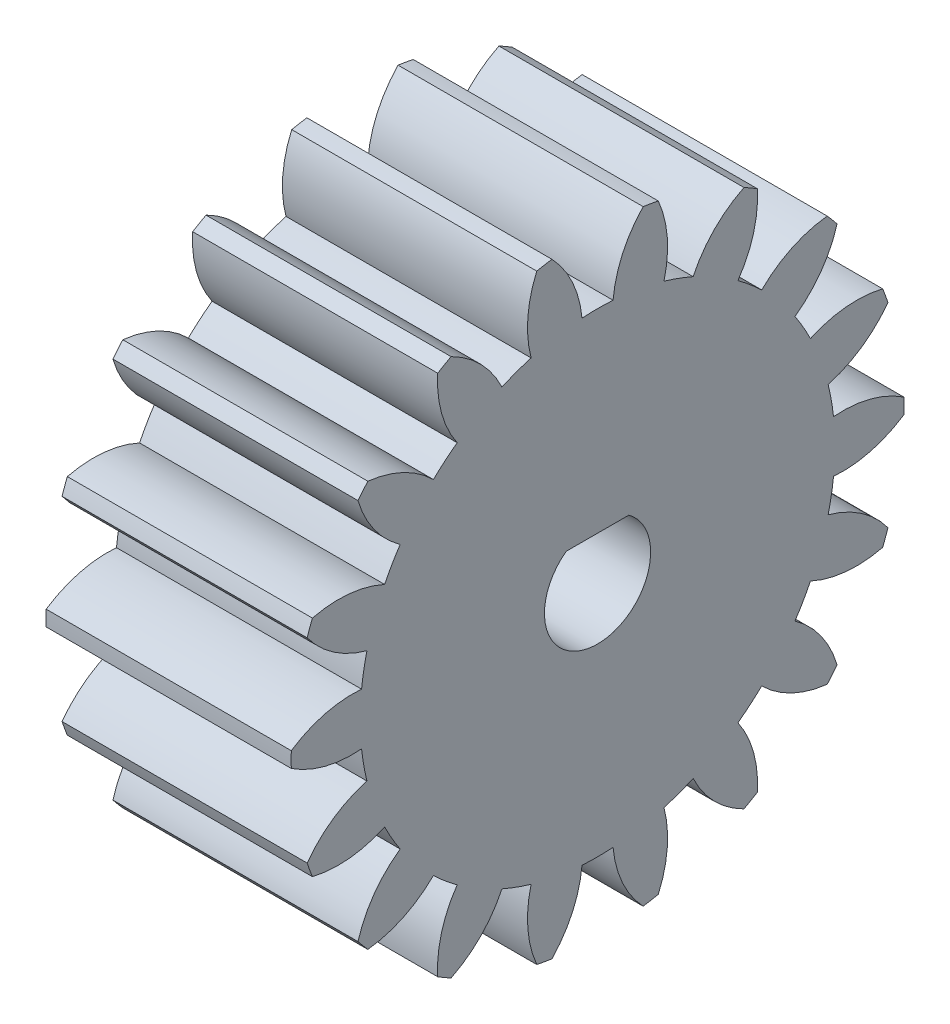
SolidWorks part; units mm, degrees
ref_plane "Plane1" through (0, 0, 0) normal (0, 0, 1) x (1, 0, 0)
ref_plane "Plane2" through (0, 0, 0) normal (0, 1, 0) x (1, 0, 0)
ref_plane "Plane3" through (0, 0, 0) normal (1, 0, 0) x (0, 0, -1)
other "Configuration Table"
sketch "HoldingSke" plane through (0, 0, 0) normal (0, 1, 0) x (1, 0, 0)
  line L0 (0, 0) -> (0.634, -0.206)
  line L1 (-15, 0) -> (100, 0) construction
  line L2 (0, 0) -> (-2.1039, 2.3779)
  line L3 (0, 0) -> (-11.863, 4.5341)
  line L4 (0, 0) -> (8.2133, 2.6687)
  line L5 (0, 0) -> (-46.8476, -17.4728)
  line L6 (0, 0) -> (-9.9476, -6.7116)
  line L7 (-2.1039, 2.3779) -> (8.6586, 51.2059)
  line L8 (-76.2, 54.61) -> (-75.3, 54.61)
  line L9 (-71.009, 38.7566) -> (-53.1078, 45.2721)
  line L10 (-76.2, 71.12) -> (104.1128, 71.12)
  line L11 (0, 0) -> (-12, 0)
  line L12 (-76.2, 101.6) -> (-76.147, 101.6)
  line L13 (24.9733, 27.94) -> (52.9518, 28.4284)
  line L14 (24.9733, 27.94) -> (24.9743, 27.94)
  line L15 (24.9733, 27.94) -> (100.4006, 29.5858)
  line L16 (-63.627, -1.5) -> (-12.827, -1.5)
  circle A0 centre (0, 0) radius 2.5
  circle A1 centre (0, 0) radius 11.624
  circle A2 centre (0, 0) radius 37.5
  circle A3 centre (0, 0) radius 2.5
  dimension "MHD" = 23.248
  dimension "Hub_dia" = 75
  dimension "Bore" = 5
  dimension "MBD" = 5
  dimension "Num_teeth" = 18
  dimension "Pitch" = 0.6667
  dimension "Overall_len" = 50
  dimension "Show_teeth" = 18
  dimension "Thickness" = 12
  dimension "OAL" = 50.0001
  dimension "T_dim" = 0.9
  dimension "Ap" = 20
  dimension "H" = 19.05
  dimension "Pitch_radius" = 180.3128
  dimension "Width" = 12
  dimension "Backlash" = 0.053
  dimension "Addendum_fac" = 1
  dimension "Dedendum_fac" = 1.25
  dimension "Clearance_fac" = 0.25
  dimension "Dedendum_add" = 0.001
  dimension "Module" = 1.5
sketch "BasProSke" plane through (0, 0, 0) normal (0, 1, 0) x (1, 0, 0)
  line L0 (-10, 0) -> (60, 0) construction
  line L1 (0, 0) -> (0, 15)
  line L2 (0, 0) -> (12, 0)
  line L3 (12, 0) -> (12, 15)
  line L4 (12, 15) -> (0, 15)
  dimension "Thickness" = 12
  dimension "Diameter" = 30
revolve "Base-Revolve" add sketch "BasProSke" angle 360 about L0
sketch "TooCutSke" plane through (0, 0, 0) normal (1, 0, 0) x (0, 0, -1)
  line L1 (0, 0) -> (0, 107) construction
  line L2 (0, 0) -> (-1.2693, 13.4402) construction
  line L3 (0, 0) -> (-4.6734, 26.504) construction
  line L4 (-1.2693, 13.4402) -> (-2.3367, 13.252) construction
  arc A0 (0.76, 11.5991) -> (-0.76, 11.5991) centre (0, 0) ccw
  arc A1 (2.2542, 14.8553) -> (-2.2542, 14.8553) centre (0, 0) ccw
  circle A2 centre (0, 0) radius 13.5 construction
  circle A3 centre (0, 0) radius 12.6859 construction
  arc A4 (-0.76, 11.5991) -> (-2.2542, 14.8553) centre (-6.1371, 11.1026) ccw
  arc A5 (2.2542, 14.8553) -> (0.76, 11.5991) centre (6.1371, 11.1026) ccw
  dimension "Root_dia" = 23.248
  dimension "Overcut_dia" = 30.0508
  dimension "Pitch_dia" = 27
  dimension "Base_dia" = 25.3717
  dimension "Flank_rad" = 5.4
  dimension "Half_ang" = 10
  dimension "Half_CT" = 1.0839
extrude "ToothCut" cut sketch "TooCutSke" along normal through all
fillet "Breaks" [suppressed] radius 0.03
fillet "RootFillets" [suppressed] radius 0.376
pattern_circular "TeethCuts" count 18 every 20 about axis through (-10, 0, 0) along (1, 0, 0) of "ToothCut", "RootFillets", "Breaks"
sketch "HubNeaOneSke" plane through (0, 0, 0) normal (-1, 0, 0) x (0, 0, 1)
  circle A0 centre (0, 0) radius 11.624
  dimension "Diameter" = 23.248
extrude "HubNearOne" [suppressed] add sketch "HubNeaOneSke" along normal blind 38.0001
sketch "HubNeaBotSke" plane through (0, 0, 0) normal (-1, 0, 0) x (0, 0, 1)
  circle A0 centre (0, 0) radius 11.624
  dimension "Diameter" = 23.248
extrude "HubNearBoth" [suppressed] add sketch "HubNeaBotSke" along normal blind 19
ref_plane "FarPln" through (12, 0, 0) normal (1, 0, 0) x (0, 0, -1)
sketch "HubFarSke" plane through (12, 0, 0) normal (1, 0, 0) x (0, 0, -1)
  circle A0 centre (0, 0) radius 11.624
  dimension "Diameter" = 23.248
extrude "HubFar" [suppressed] add sketch "HubFarSke" along normal blind 19
sketch "BorSke" plane through (0, 0, 0) normal (1, 0, 0) x (0, 0, -1)
  circle A0 centre (0, 0) radius 2.5
  dimension "Diameter" = 5
extrude "Bore" cut sketch "BorSke" along normal mid plane 100.0001
sketch "KeySke" plane through (0, 0, 0) normal (1, 0, 0) x (0, 0, -1)
  line L0 (-1, 0) -> (-1, 3.4)
  line L1 (-1, 3.4) -> (1, 3.4)
  line L2 (1, 3.4) -> (1, 0)
  line L3 (0, 0) -> (0, 34) construction
  line L4 (-1, 0) -> (1, 0)
  dimension "Offset" = 3.4
  dimension "Width" = 2
extrude "Keyway" [suppressed] cut sketch "KeySke" along normal mid plane 100.0001
pattern_circular "Keyway2" [suppressed] count 2 every 90 about axis through (-10, 0, 0) along (1, 0, 0)
sketch "草圖1" plane through (12, 0, 0) normal (1, 0, 0) x (0, 0, -1)
  circle A0 centre (0, 0) radius 2.6
  dimension "D1" = 5.2
extrude "除料-伸長1" cut sketch "草圖1" against normal through all
sketch "草圖2" plane through (12, 0, 0) normal (1, 0, 0) x (0, 0, -1)
  line L1 (0, 2.1) -> (1.533, 2.1)
  line L2 (0, 2.1) -> (-1.533, 2.1)
  arc A0 (1.533, 2.1) -> (-1.533, 2.1) centre (0, 0) ccw
  dimension "D2" = 5.2
extrude "填料-伸長2" add sketch "草圖2" against normal through all
equation "' \"Module@HoldingSke\" = 6.35"
equation "' \"Num_teeth@HoldingSke\" = 12"
equation "' \"Ap@HoldingSke\" =  20"
equation "' \"Ap@HoldingSke\" = 20"
equation "' \"Width@HoldingSke\" = 0.5 * 25.4"
equation "' \"Hub_dia@HoldingSke\"= 1 * 25.4"
equation "' \"Hub_dia@HoldingSke\" = 1 * 25.4"
equation "' \"Overall_len@HoldingSke\" = 1.0 * 25.4"
equation "' \"Bore@HoldingSke\" = 0.75 * 25.4"
equation "' \"T_dim@HoldingSke\" = 0.1 * 25.4"
equation "' \"Width@KeySke\" = 0.25 * 25.4"
equation "' \"Show_teeth@HoldingSke\" = 13"
equation "' \"Backlash@HoldingSke\" = 0.009 * 25.4"
equation "' \"Addendum_fac@HoldingSke\" = 1.0"
equation "' \"Dedendum_fac@HoldingSke\" = 1.25"
equation "' \"Dedendum_add@HoldingSke\" = 0.00005 * 25.4"
equation "' \"Clearance_fac@HoldingSke\" = 0.25"
equation "\"Pitch@HoldingSke\" = 1 / \"Module@HoldingSke\""
equation "\"Overcut_dia@TooCutSke\" = (\"Num_teeth@HoldingSke\" + 2 * \"Addendum_fac@HoldingSke\") / \"Pitch@HoldingSke\" + 0.002 * 25.4"
equation "\"Pitch_dia@TooCutSke\" = \"Num_teeth@HoldingSke\" / \"Pitch@HoldingSke\""
equation "\"Base_dia@TooCutSke\" = \"Num_teeth@HoldingSke\" / \"Pitch@HoldingSke\" * cos((\"Ap@HoldingSke\"  * 3.14159265 / 180))"
equation "\"Root_dia@TooCutSke\" = (\"Num_teeth@HoldingSke\" + 2) / \"Pitch@HoldingSke\" - 2 * (\"Addendum_fac@HoldingSke\" + \"Dedendum_fac@HoldingSke\") / \"Pitch@HoldingSke\" - \"Dedendum_add@HoldingSke\" * 2"
equation "\"Half_ang@TooCutSke\" = 180 / \"Num_teeth@HoldingSke\""
equation "\"Half_CT@TooCutSke\" = \"Num_teeth@HoldingSke\" / \"Pitch@HoldingSke\" * sin((3.14159265 / 2 / \"Num_teeth@HoldingSke\")) / 2 - 7 * \"Backlash@HoldingSke\" / 4"
equation "\"Flank_rad@TooCutSke\" = \"Num_teeth@HoldingSke\" / \"Pitch@HoldingSke\" / 5"
equation "\"Radius@RootFillets\" = \"Clearance_fac@HoldingSke\" / \"Pitch@HoldingSke\" + \"Dedendum_add@HoldingSke\""
equation "\"Break_rad@Breaks\" = 0.02 / \"Pitch@HoldingSke\""
equation "\"Thickness@HoldingSke\" = \"Width@HoldingSke\""
equation "\"OAL@HoldingSke\" = \"Thickness@HoldingSke\""
equation "\"MHD@HoldingSke\" = (\"Num_teeth@HoldingSke\" + 2) / \"Pitch@HoldingSke\" - 2 * (\"Addendum_fac@HoldingSke\" + \"Dedendum_fac@HoldingSke\")  / \"Pitch@HoldingSke\" - \"Dedendum_add@HoldingSke\" * 2"
equation "\"MBD@HoldingSke\" = (\"Num_teeth@HoldingSke\" + 2) / \"Pitch@HoldingSke\" - 2 * (\"Addendum_fac@HoldingSke\" + \"Dedendum_fac@HoldingSke\")  / \"Pitch@HoldingSke\" - \"Dedendum_add@HoldingSke\" * 2 - 0.002 * 25.4"
equation "\"MHD@HoldingSke\" = ((sgn( \"MHD@HoldingSke\" - \"Hub_dia@HoldingSke\" )-1)*( \"MHD@HoldingSke\" - \"Hub_dia@HoldingSke\" ))/-2+ \"Hub_dia@HoldingSke\""
equation "\"MBD@HoldingSke\" = ((sgn( \"MBD@HoldingSke\" - \"Bore@HoldingSke\" )-1)*( \"MBD@HoldingSke\" - \"Bore@HoldingSke\" ))/-2+ \"Bore@HoldingSke\""
equation "\"OAL@HoldingSke\" = ((sgn( \"OAL@HoldingSke\" - \"Overall_len@HoldingSke\" )+1)*( \"OAL@HoldingSke\" - \"Overall_len@HoldingSke\" ))/2 + \"Overall_len@HoldingSke\" + 0.000002 * 25.4"
equation "\"Num_teeth@TeethCuts\" = int( \"Show_teeth@HoldingSke\" ) + 1"
equation "\"Num_teeth@TeethCuts\" = ((sgn( \"Num_teeth@TeethCuts\" - \"Num_teeth@HoldingSke\" )-1)*( \"Num_teeth@TeethCuts\" - \"Num_teeth@HoldingSke\" ))/-2+ \"Num_teeth@HoldingSke\""
equation "\"Num_teeth@TeethCuts\" = ((sgn( \"Num_teeth@TeethCuts\" - 2.0)+1)*( \"Num_teeth@TeethCuts\" - 2.0))/2 +2.0"
equation "\"Angle@TeethCuts\" = 360.0 / \"Num_teeth@HoldingSke\""
equation "\"Diameter@BasProSke\" = (\"Num_teeth@HoldingSke\" + 2 * \"Addendum_fac@HoldingSke\") / \"Pitch@HoldingSke\""
equation "\"Thickness@BasProSke\"  = \"Thickness@HoldingSke\""
equation "' \"Fillet_rad@BasProSke\" =  \"Thickness@HoldingSke\" * 0.05"
equation "' \"Fillet_rad@BasProSke\" = \"Thickness@HoldingSke\" * 0.05"
equation "\"MHD@HoldingSke\" = ((sgn( \"MHD@HoldingSke\" - \"Root_dia@TooCutSke\" )-1)*( \"MHD@HoldingSke\" - \"Root_dia@TooCutSke\" ))/-2+ \"Root_dia@TooCutSke\""
equation "\"Diameter@HubNeaOneSke\" = \"MHD@HoldingSke\""
equation "\"Length@HubNearOne\" = \"OAL@HoldingSke\" - \"Thickness@BasProSke\""
equation "\"Diameter@HubNeaBotSke\" = \"MHD@HoldingSke\""
equation "\"Length@HubNearBoth\" = ( \"OAL@HoldingSke\" - \"Thickness@BasProSke\" ) / 2.0"
equation "\"Thickness@FarPln\" = \"Thickness@BasProSke\""
equation "\"Diameter@HubFarSke\" = \"MHD@HoldingSke\""
equation "\"Length@HubFar\" = ( \"OAL@HoldingSke\" - \"Thickness@BasProSke\" ) / 2.0"
equation "\"Diameter@BorSke\" = \"MBD@HoldingSke\""
equation "\"D1@Bore\" = \"OAL@HoldingSke\" * 2.0"
equation "\"D1@Keyway\" = \"OAL@HoldingSke\" * 2.0"
equation "\"Offset@KeySke\" = \"T_dim@HoldingSke\" + \"MBD@HoldingSke\" / 2.0"
